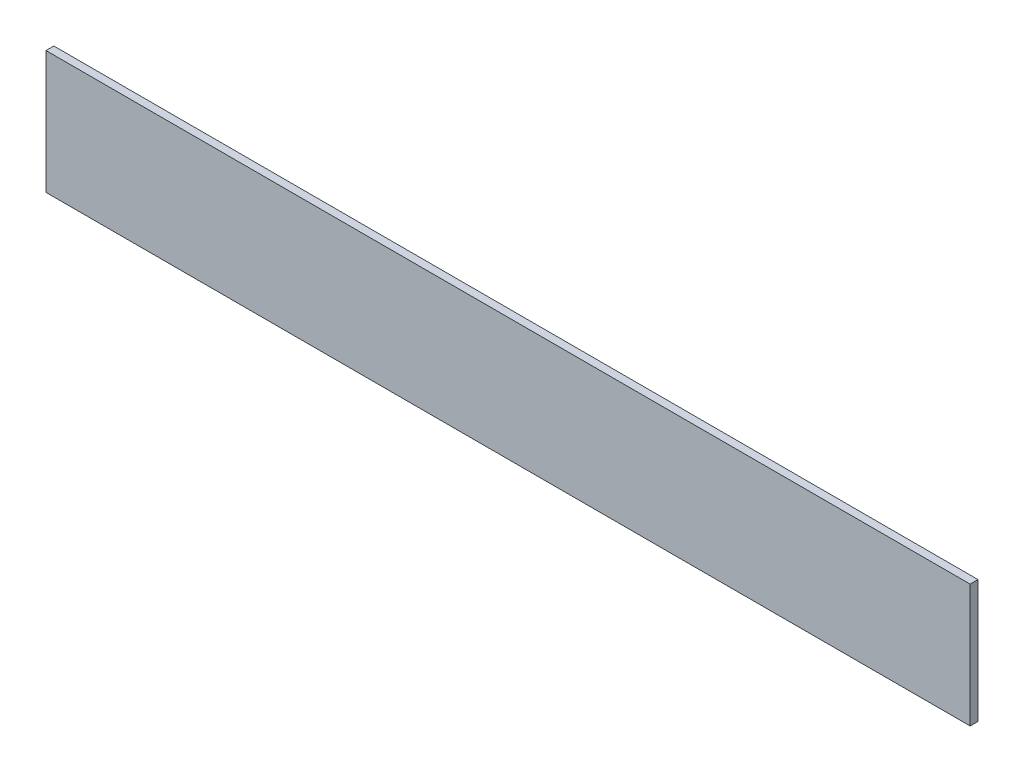
SolidWorks part; units mm, degrees
ref_plane "Front Plane" through (0, 0, 0) normal (0, 0, 1) x (1, 0, 0)
ref_plane "Top Plane" through (0, 0, 0) normal (0, 1, 0) x (1, 0, 0)
ref_plane "Right Plane" through (0, 0, 0) normal (1, 0, 0) x (0, 0, -1)
sketch "Sketch1" plane through (0, 0, 0) normal (0, 1, 0) x (1, 0, 0)
  line L1 (-191.0326, -1.6235) -> (191.0326, -1.6235)
  line L2 (-191.0326, -1.6235) -> (-191.0326, 1.6235)
  line L3 (-191.0326, 1.6235) -> (191.0326, 1.6235)
  line L4 (191.0326, -1.6235) -> (191.0326, 1.6235)
  line L5 (-191.0326, -1.6235) -> (191.0326, 1.6235) construction
  line L6 (-191.0326, 1.6235) -> (191.0326, -1.6235) construction
  point P0 (0, 0)
extrude "Boss-Extrude1" add sketch "Sketch1" along normal blind 50.8
